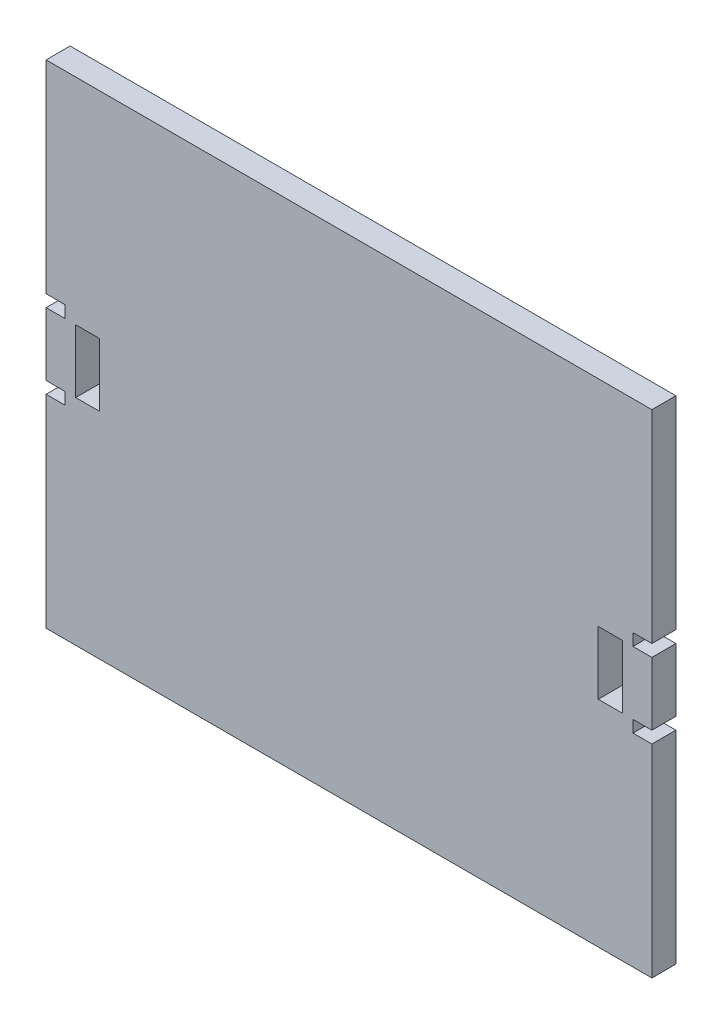
SolidWorks part; units mm, degrees
ref_plane "Front Plane" through (0, 0, 0) normal (0, 0, 1) x (1, 0, 0)
ref_plane "Top Plane" through (0, 0, 0) normal (0, 1, 0) x (1, 0, 0)
ref_plane "Right Plane" through (0, 0, 0) normal (1, 0, 0) x (0, 0, -1)
sketch "Sketch1" plane through (0, 0, 0) normal (0, 0, 1) x (1, 0, 0)
  line L0 (-72.175, 73.33) -> (-80, 73.33) construction
  line L1 (-80, 0) -> (80, 0)
  line L4 (80, 0) -> (80, 53.52)
  line L9 (65.825, 73.33) -> (72.175, 73.33)
  line L10 (65.825, 73.33) -> (65.825, 56.67)
  line L11 (65.825, 56.67) -> (72.175, 56.67)
  line L12 (72.175, 73.33) -> (72.175, 56.67)
  line L13 (72.175, 56.67) -> (80, 56.67) construction
  line L14 (-65.825, 73.33) -> (-65.825, 130) construction
  line L15 (65.825, 56.67) -> (65.825, 0) construction
  line L16 (-65.825, 56.67) -> (-65.825, 0) construction
  line L17 (65.825, 73.33) -> (65.825, 130) construction
  line L18 (80, 76.505) -> (75, 76.505)
  line L19 (75, 76.505) -> (75, 73.33)
  line L20 (75, 73.33) -> (80, 73.33)
  line L21 (80, 56.67) -> (75, 56.67)
  line L22 (75, 56.67) -> (75, 53.52)
  line L23 (75, 53.52) -> (80, 53.52)
  line L24 (72.175, 73.33) -> (80, 73.33) construction
  line L25 (80, 76.505) -> (80, 130)
  line L26 (80, 56.67) -> (80, 73.33)
  line L27 (0, 0) -> (0, 130) construction
  line L29 (-72.175, 56.67) -> (-80, 56.67) construction
  line L43 (-80, 130) -> (80, 130)
  line L44 (-80, 56.67) -> (-80, 73.33)
  line L45 (-80, 76.505) -> (-80, 130)
  line L46 (-75, 53.52) -> (-80, 53.52)
  line L47 (-75, 56.67) -> (-75, 53.52)
  line L48 (-80, 56.67) -> (-75, 56.67)
  line L49 (-75, 73.33) -> (-80, 73.33)
  line L50 (-75, 76.505) -> (-75, 73.33)
  line L51 (-80, 76.505) -> (-75, 76.505)
  line L52 (-72.175, 73.33) -> (-72.175, 56.67)
  line L53 (-65.825, 56.67) -> (-72.175, 56.67)
  line L54 (-65.825, 73.33) -> (-65.825, 56.67)
  line L55 (-65.825, 73.33) -> (-72.175, 73.33)
  line L56 (-80, 0) -> (-80, 53.52)
  point P0 (-65.825, 123.7255)
  dimension "D10" = 3.15
  dimension "D1" = 130
  dimension "D2" = 80
  dimension "D3" = 7.825
  dimension "D5" = 6.35
  dimension "D6" = 16.66
  dimension "D8" = 5
  dimension "D9" = 3.175
  dimension "D11" = 5
extrude "Boss-Extrude1" add sketch "Sketch1" along normal blind 6.35
